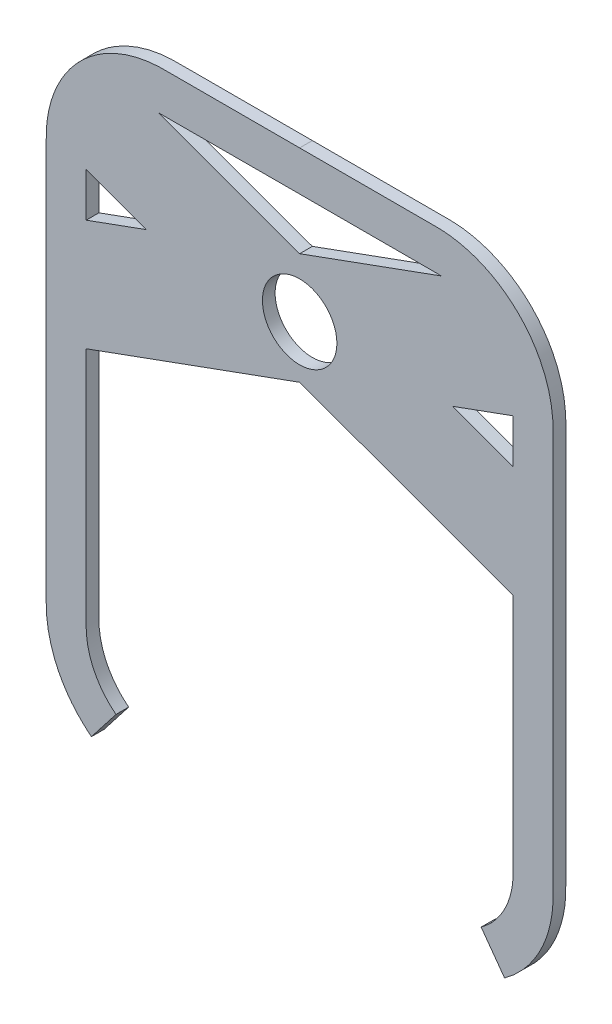
SolidWorks part; units mm, degrees
material "Фанера"
ref_plane "Front Plane" through (0, 0, 0) normal (0, 0, 1) x (1, 0, 0)
ref_plane "Top Plane" through (0, 0, 0) normal (0, 1, 0) x (1, 0, 0)
ref_plane "Right Plane" through (0, 0, 0) normal (1, 0, 0) x (0, 0, -1)
sketch "Эскиз1" plane through (0, 0, 0) normal (0, 0, 1) x (1, 0, 0)
  line L0 (-45.8381, 1.6179) -> (-40.4357, 8.5643)
  line L1 (39.9636, 8.2102) -> (45.1219, 1.0805)
  line L2 (0, 155.6618) -> (0, 34.4561) construction
  line L3 (0, 128.0052) -> (86.618, 128.0052) construction
  line L4 (-31.1435, 127.9666) -> (0, 116.6313)
  line L5 (-47, 109.2179) -> (-33.6841, 104.3713)
  line L6 (47, 109.2179) -> (33.6841, 104.3713)
  line L7 (31.1435, 127.9666) -> (0, 116.6313)
  line L8 (-33.6841, 104.3713) -> (-47, 99.5247)
  line L9 (0, 92.1113) -> (47, 75.0047)
  line L10 (33.6841, 104.3713) -> (47, 99.5247)
  line L11 (0, 92.1113) -> (-47, 75.0047)
  line L12 (-47, 109.2179) -> (-50.4323, 120.4968)
  line L13 (-50.4323, 120.4968) -> (-33.6841, 132.0604)
  line L14 (-33.6841, 132.0604) -> (-31.1435, 127.9666)
  line L15 (-47, 99.5247) -> (-51.8778, 93.1536)
  line L16 (-51.8778, 93.1536) -> (-50.4323, 75.0047)
  line L17 (-50.4323, 75.0047) -> (-47, 75.0047)
  line L18 (31.1435, 127.9666) -> (40.7246, 130.8823)
  line L19 (40.7246, 130.8823) -> (51.2312, 117.7263)
  line L20 (51.2312, 117.7263) -> (47, 109.2179)
  line L21 (47, 99.5247) -> (50.1131, 83.558)
  line L22 (50.1131, 83.558) -> (47, 75.0047)
  circle A1 centre (0, 103.6369) radius 8.2
  circle A2 centre (0, 103.6369) radius 4.3081 construction
  spline S2 degree 3 poles (44.653, 1.7287) (45.7274, 2.506) (47.9893, 4.4335) (50.9208, 8.0055) (53.2459, 12.3555) (54.6778, 17.0756) (55, 20.3481) (55, 51.6579) (55, 81.3315) (55, 112.6414) (54.6778, 115.9139) (53.2459, 120.6339) (50.9208, 124.984) (47.7917, 128.7968) (43.9788, 131.926) (39.6288, 134.2511) (34.9087, 135.6829) (31.6362, 136.0052) (20, 136.0052) (10, 136.0052) (0, 136.0052) knots 0 0 0 0 0.017483 0.039054 0.060625 0.082196 0.103767 0.103767 0.494964 0.494964 0.516535 0.538106 0.559677 0.581248 0.602819 0.62439 0.645961 0.667533 0.667533 0.799365 0.799365 0.799365 0.799365 construction
  spline S3 degree 3 poles (0, 136.0052) (-10, 136.0052) (-20, 136.0052) (-31.6362, 136.0052) (-34.9087, 135.6829) (-39.6288, 134.2511) (-43.9788, 131.926) (-47.7917, 128.7968) (-50.9208, 124.984) (-53.2459, 120.6339) (-54.6778, 115.9139) (-55, 112.6414) (-55, 81.3315) (-55, 51.6579) (-55, 20.3481) (-54.6778, 17.0756) (-53.2459, 12.3555) (-50.9208, 8.0055) (-48.1737, 4.6582) (-46.1655, 2.8859) (-45.347, 2.2494) knots 0 0 0 0 0.131833 0.131833 0.153404 0.174975 0.196546 0.218117 0.239689 0.26126 0.282831 0.304402 0.304402 0.695598 0.695598 0.717169 0.73874 0.760311 0.781883 0.795553 0.795553 0.795553 0.795553 construction
  spline S4 degree 1 poles (45.1219, 1.0805) (0, 136.8052) knots 0 0 1 1 construction
  spline S5 degree 1 poles (0, 136.8052) (-45.8381, 1.6179) knots 0 0 1 1 construction
  spline S6 degree 3 poles (45.1219, 1.0805) (46.7028, 2.2243) (49.6149, 4.8819) (52.9632, 9.7416) (54.7718, 14.3199) (55.5688, 18.1517) (55.7992, 20.5977) (55.8001, 22.537) (55.7999, 24.4209) (55.8, 26.7948) (55.8, 29.6353) (55.8, 33.4256) (55.8, 38.1624) (55.8, 43.847) (55.8, 49.5315) (55.8, 57.1108) (55.8, 66.585) (55.8, 76.0591) (55.8, 83.6385) (55.8, 89.323) (55.8, 95.0076) (55.8001, 99.7443) (55.7999, 103.5347) (55.8004, 106.3748) (55.7989, 108.7501) (55.802, 110.6311) (55.7894, 112.5824) (55.5402, 115.0208) (54.7159, 118.8491) (52.8747, 123.4128) (49.4893, 128.2498) (45.1003, 132.1996) (40.7946, 134.5811) (37.0952, 135.8686) (34.2273, 136.5111) (31.7978, 136.7802) (29.8327, 136.8098) (27.9551, 136.8025) (25.5782, 136.806) (21.7918, 136.8047) (17.0531, 136.8053) (9.4744, 136.8051) (3.7897, 136.8052) (0, 136.8052) knots 0 0 0 0 0.02498 0.04996 0.074941 0.087431 0.099921 0.106166 0.112411 0.124901 0.137391 0.149881 0.174861 0.199841 0.224822 0.249802 0.299762 0.349722 0.374703 0.399683 0.424663 0.449643 0.462133 0.474623 0.487113 0.493358 0.499603 0.512094 0.524584 0.549564 0.574544 0.599524 0.624504 0.636994 0.649484 0.661975 0.66822 0.674465 0.686955 0.699445 0.724425 0.749405 0.799365 0.799365 0.799365 0.799365
  spline S7 degree 3 poles (0, 136.8052) (-3.7716, 136.8052) (-9.4292, 136.8051) (-16.9718, 136.8053) (-21.6877, 136.8049) (-25.4565, 136.8057) (-27.8209, 136.8036) (-29.6919, 136.8079) (-31.6381, 136.7905) (-34.0623, 136.5374) (-36.9193, 135.9176) (-40.6107, 134.6632) (-44.9145, 132.328) (-49.3184, 128.438) (-52.737, 123.6586) (-54.6206, 119.1402) (-55.4881, 115.3363) (-55.7654, 112.9236) (-55.8064, 110.9599) (-55.7963, 109.0933) (-55.8012, 106.7266) (-55.7997, 103.9009) (-55.8002, 100.1284) (-55.7999, 95.4143) (-55.8, 89.7568) (-55.8, 84.0995) (-55.8, 76.5563) (-55.8, 67.1273) (-55.8, 55.8125) (-55.8001, 46.3835) (-55.7999, 38.8403) (-55.8004, 33.1831) (-55.7989, 28.468) (-55.8015, 25.1689) (-55.7973, 23.2815) (-55.8144, 21.4024) (-55.6793, 18.9377) (-54.9979, 15.111) (-53.3484, 10.4948) (-50.1767, 5.5527) (-47.3711, 2.8101) (-45.8381, 1.6179) knots 0 0 0 0 0.049722 0.074583 0.099444 0.111875 0.124305 0.13052 0.136736 0.149166 0.161597 0.174027 0.198888 0.223749 0.24861 0.273471 0.285902 0.298332 0.304547 0.310763 0.323193 0.335624 0.348054 0.372915 0.397776 0.422637 0.447498 0.49722 0.546942 0.596664 0.621525 0.646386 0.671247 0.683678 0.689893 0.696108 0.708539 0.720969 0.745831 0.770692 0.795553 0.795553 0.795553 0.795553
  spline S8 degree 1 poles (39.9636, 8.2102) (0, 128.0052) knots 0 0 1 1 construction
  spline S9 degree 1 poles (0, 128.0052) (-40.4357, 8.5643) knots 0 0 1 1 construction
  spline S10 degree 3 poles (39.9636, 8.2102) (41.0054, 8.9639) (42.9242, 10.7147) (44.7631, 13.3844) (45.8458, 15.7264) (46.3523, 17.2593) (46.6512, 18.5129) (46.8213, 19.4635) (46.9374, 20.4231) (46.9834, 21.1505) (46.9969, 21.6291) (46.9997, 21.838) (47.0001, 21.9828) (47, 22.2422) (47, 22.6426) (47, 23.2426) (47, 24.1869) (47, 25.3727) (47, 27.2669) (47, 29.6358) (47, 33.4253) (47, 38.1625) (47, 43.847) (47, 49.5315) (47, 57.1108) (47, 65.1282) (47, 72.1981) (47, 75.9878) (47, 79.3394) (47, 83.6385) (47, 89.323) (47, 94.3816) (47, 98.019) (47, 99.9984) (47, 101.5718) (47, 103.619) (47, 105.9022) (47, 107.7987) (47, 108.9786) (47, 109.9351) (46.9998, 110.504) (47.0003, 111.0254) (46.9986, 111.3047) (46.9825, 111.8946) (46.9257, 112.6841) (46.7617, 113.9693) (46.4214, 115.5413) (45.8003, 117.3774) (44.7006, 119.7115) (42.8415, 122.3685) (39.9491, 124.9708) (37.1132, 126.5398) (34.6745, 127.3879) (33.1011, 127.7416) (31.8255, 127.9161) (31.0164, 127.9798) (30.4624, 128.0003) (30.1677, 128.0046) (30.0279, 128.0053) (29.7806, 128.0051) (29.4896, 128.0052) (29.0139, 128.0052) (28.1862, 128.0052) (27.0012, 128.0052) (25.1067, 128.0052) (22.738, 128.0052) (19.8958, 128.0052) (16.1061, 128.0052) (11.369, 128.0052) (5.6845, 128.0052) (1.8948, 128.0052) (0, 128.0052) knots 0 0 0 0 0.02498 0.04996 0.06245 0.074941 0.081186 0.087431 0.093676 0.099921 0.101482 0.103043 0.103824 0.104604 0.106166 0.109288 0.112411 0.118656 0.124901 0.137391 0.149881 0.174861 0.199841 0.224822 0.249802 0.299762 0.330517 0.343007 0.349722 0.374703 0.399683 0.424663 0.441391 0.447636 0.450758 0.462133 0.474623 0.480868 0.487113 0.490236 0.493358 0.49492 0.496481 0.499603 0.505848 0.512094 0.524584 0.537074 0.549564 0.574544 0.599524 0.624504 0.636994 0.649484 0.655729 0.661975 0.665097 0.666658 0.667439 0.66822 0.669781 0.671342 0.674465 0.68071 0.686955 0.699445 0.711935 0.724425 0.749405 0.774385 0.799365 0.799365 0.799365 0.799365
  spline S11 degree 3 poles (0, 128.0052) (-1.8858, 128.0052) (-5.6574, 128.0052) (-11.3148, 128.0052) (-16.0293, 128.0052) (-19.8009, 128.0052) (-22.6296, 128.0052) (-24.9866, 128.0052) (-26.8729, 128.0052) (-28.0504, 128.0051) (-28.9956, 128.0052) (-29.5789, 128.0049) (-30.0627, 128.0055) (-30.343, 128.0028) (-30.6865, 127.9927) (-31.015, 127.9754) (-31.3353, 127.9538) (-31.8833, 127.9053) (-32.9935, 127.7615) (-34.5576, 127.4202) (-36.9928, 126.5937) (-39.8265, 125.0554) (-42.729, 122.4922) (-44.606, 119.868) (-45.7266, 117.556) (-46.3656, 115.7381) (-46.7237, 114.1738) (-46.9027, 112.9043) (-46.9697, 112.1019) (-46.9927, 111.5459) (-46.9993, 111.2181) (-47.0002, 111.0008) (-46.9999, 110.6109) (-47, 110.1558) (-47, 109.7444) (-47, 109.3357) (-47, 108.8598) (-47, 107.972) (-47, 106.257) (-47, 103.9005) (-47, 100.1286) (-47, 95.4143) (-47, 89.7568) (-47, 84.0994) (-47, 76.5563) (-47, 67.1273) (-47, 57.6983) (-47, 50.1551) (-47, 44.4977) (-47, 38.8403) (-47, 34.1258) (-47, 30.3543) (-47, 27.9969) (-47, 26.1114) (-47, 24.6959) (-47, 23.5209) (-47, 22.6894) (-47, 22.2859) (-47, 22.0357) (-47, 21.8595) (-46.9975, 21.6672) (-46.9893, 21.3437) (-46.9628, 20.785) (-46.8911, 19.9846) (-46.7511, 19.0327) (-46.4933, 17.7782) (-46.0373, 16.2361) (-45.0362, 13.8731) (-43.2949, 11.1566) (-41.4459, 9.35) (-40.4357, 8.5643) knots 0 0 0 0 0.024861 0.049722 0.074583 0.087014 0.099444 0.111875 0.11809 0.124305 0.127413 0.13052 0.132074 0.133628 0.136736 0.138453 0.140007 0.142951 0.149166 0.161597 0.174027 0.198888 0.223749 0.24861 0.261041 0.273471 0.285902 0.292117 0.298332 0.30144 0.302994 0.304547 0.306101 0.307655 0.310702 0.311479 0.313033 0.316978 0.323193 0.335624 0.348054 0.372915 0.397776 0.422637 0.447498 0.49722 0.546942 0.571803 0.596664 0.621525 0.646386 0.658817 0.671247 0.677463 0.683678 0.689893 0.693001 0.694555 0.695332 0.696108 0.697662 0.699216 0.702324 0.708539 0.714754 0.720969 0.7334 0.745831 0.770692 0.795553 0.795553 0.795553 0.795553
  point P36 (47.0469, 75.0047)
  dimension "D3" = 16.4
  dimension "D4" = 20
  dimension "D1" = 0.8
  dimension "D2" = 8
extrude "Бобышка-Вытянуть1" add sketch "Эскиз1" along normal mid plane 2.8 contours L4 S11 L5 L8 L11 L9 S10 L10 L6 L7 A1 | S11 S10 L7 L18 L19 L20 L21 L22 L1 S6 S7 L0 L17 L16 L15 L12 L13 L14 | S11 L14 L13 L12 | S11 L15 L16 L17 | S10 L20 L19 L18 L7 | S10 L22 L21
